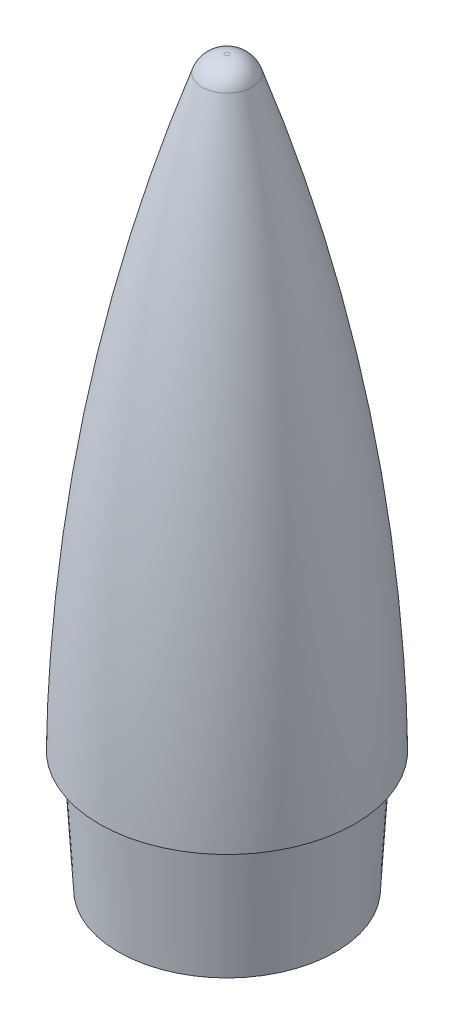
SolidWorks part; units mm, degrees
material "ABS"
ref_plane "Front" through (0, 0, 0) normal (0, 0, 1) x (1, 0, 0)
ref_plane "Top" through (0, 0, 0) normal (0, 1, 0) x (1, 0, 0)
ref_plane "Right" through (0, 0, 0) normal (1, 0, 0) x (0, 0, -1)
sketch "Sketch1" plane through (0, 0, 0) normal (0, 0, 1) x (1, 0, 0)
  line L0 (0, 0) -> (-11.43, 0)
  line L1 (-11.43, 0) -> (-12.192, 12.7)
  line L2 (-12.192, 12.7) -> (-13.462, 12.7)
  line L3 (-2.032, 76.2) -> (0, 76.2)
  line L4 (0, 76.2) -> (0, 0)
  arc A0 (-2.032, 76.2) -> (-13.462, 12.7) centre (186.4104, 9.5017) ccw
  dimension "D7" = 199.898
  dimension "D1" = 12.7
  dimension "D2" = 0.762
  dimension "D3" = 11.43
  dimension "D4" = 1.27
  dimension "D5" = 2.032
  dimension "D6" = 63.5
revolve "Revolve1" add sketch "Sketch1" angle 360 about L4
fillet "Fillet1" radius 2.54 1 edges at (0, 76.2, 2.032)
fillet "Fillet2" radius 0.508 1 edges at (0, 12.7, 12.192)
sketch "Sketch2" plane through (0, 0, 0) normal (0, -1, 0) x (1, 0, 0)
  circle A0 centre (0, 0) radius 9.525
  dimension "D1" = 19.05
extrude "Cut-Extrude1" cut sketch "Sketch2" against normal blind 25.4 draft 3
fillet "Fillet3" radius 7.62 1 edges at (0, 25.4, -8.1938)
sketch "Sketch4" plane through (0, 0, 0) normal (0, 0, 1) x (1, 0, 0)
  line L0 (9.525, 0) -> (-9.525, 0)
  line L1 (-9.525, 0) -> (9.525, 0) construction
  line L2 (-11.43, 0) -> (11.43, 0) construction
  line L3 (-9.525, 0) -> (-9.525, 2.54)
  line L4 (-9.525, 2.54) -> (9.525, 2.54)
  line L5 (9.525, 2.54) -> (9.525, 0)
  dimension "D1" = 2.54
extrude "Boss-Extrude2" add sketch "Sketch4" along normal blind 1.905 and the other way blind 1.905
fillet "Fillet4" radius 1.27 4 edges
